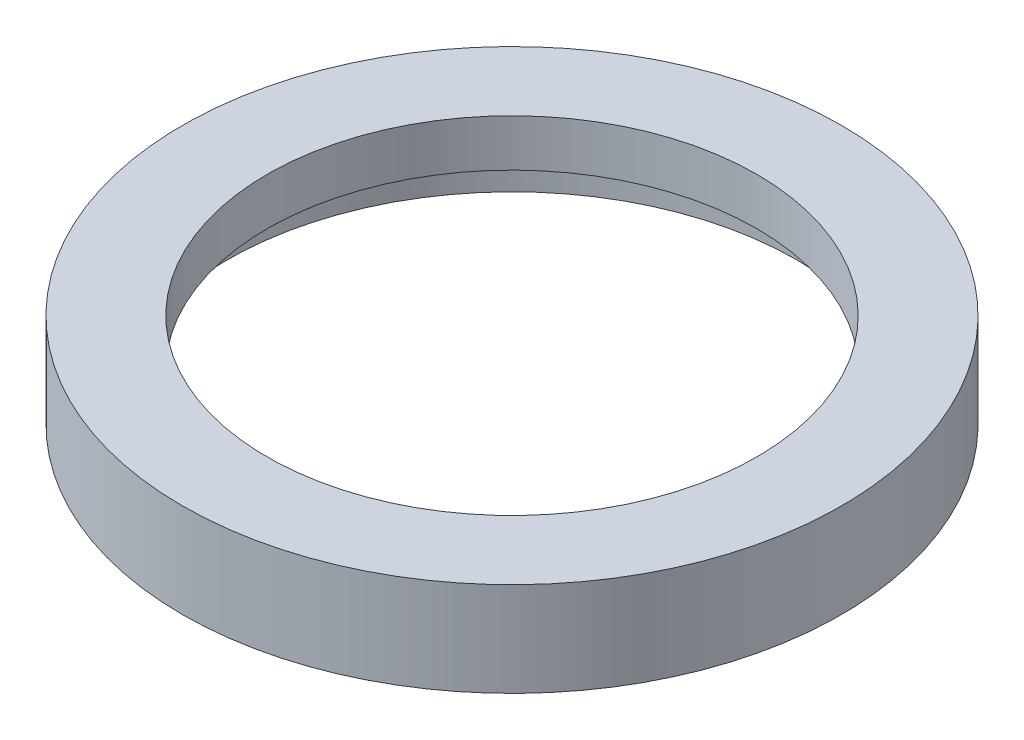
SolidWorks part; units mm, degrees
ref_plane "Front Plane" through (0, 0, 0) normal (0, 0, 1) x (1, 0, 0)
ref_plane "Top Plane" through (0, 0, 0) normal (0, 1, 0) x (1, 0, 0)
ref_plane "Right Plane" through (0, 0, 0) normal (1, 0, 0) x (0, 0, -1)
sketch "Sketch1" plane through (0, 0, 0) normal (0, 0, 1) x (1, 0, 0)
  line L0 (0, 0) -> (0, 11.6285) construction
  line L9 (-26, 0) -> (-35, 0)
  line L10 (-26, 0) -> (-26, 5)
  line L11 (-26, 5) -> (-35, 5)
  line L12 (-35, 0) -> (-35, 5)
  line L13 (-35, 0) -> (-30.25, 0)
  line L14 (-35, 0) -> (-35, -5)
  line L15 (-35, -5) -> (-30.25, -5)
  line L16 (-30.25, 0) -> (-30.25, -5)
  dimension "D1" = 35
  dimension "D2" = 26
  dimension "D3" = 30.25
  dimension "D4" = 10
  dimension "D5" = 5
revolve "Revolve1" add sketch "Sketch1" angle 360 about L0
